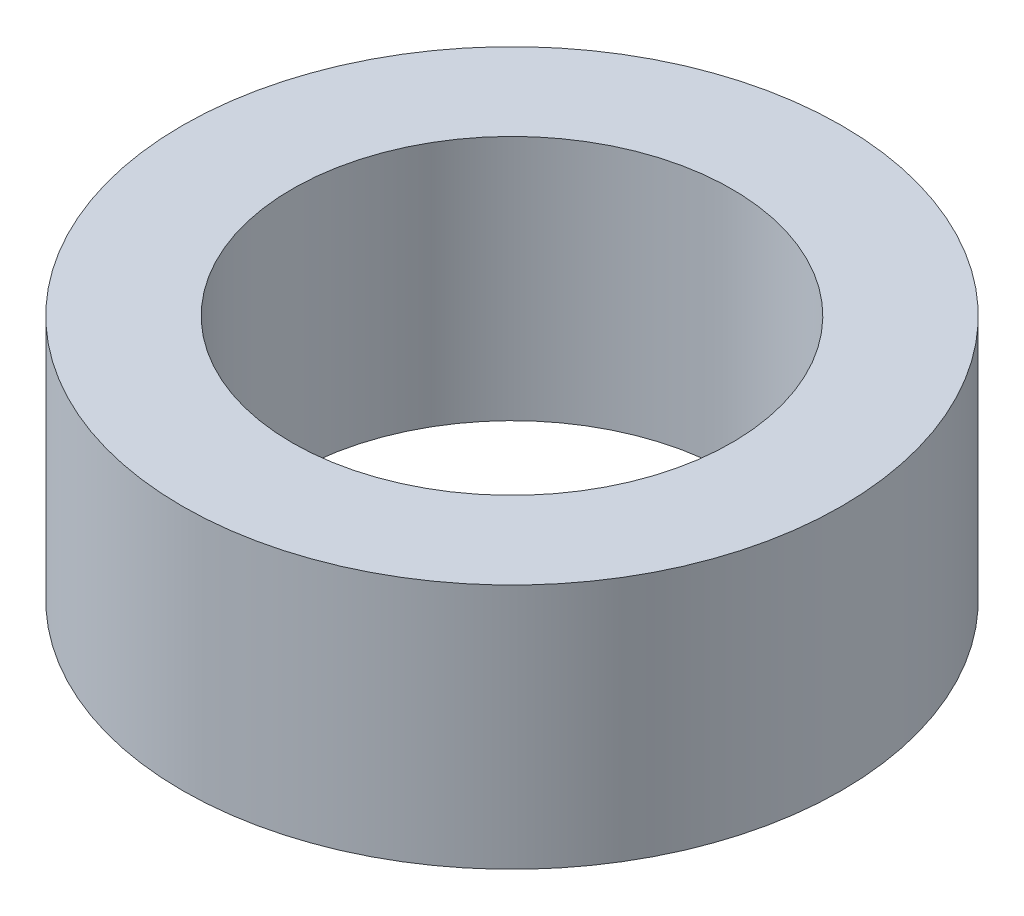
SolidWorks part; units mm, degrees
ref_plane "Front Plane" through (0, 0, 0) normal (0, 0, 1) x (1, 0, 0)
ref_plane "Top Plane" through (0, 0, 0) normal (0, 1, 0) x (1, 0, 0)
ref_plane "Right Plane" through (0, 0, 0) normal (1, 0, 0) x (0, 0, -1)
sketch "Sketch1" plane through (0, 0, 0) normal (0, 1, 0) x (1, 0, 0)
  circle A0 centre (0, 0) radius 9.525
  circle A1 centre (0, 0) radius 6.35
  dimension "D1" = 19.05
  dimension "D2" = 12.7
extrude "Boss-Extrude1" add sketch "Sketch1" along normal blind 7.112
